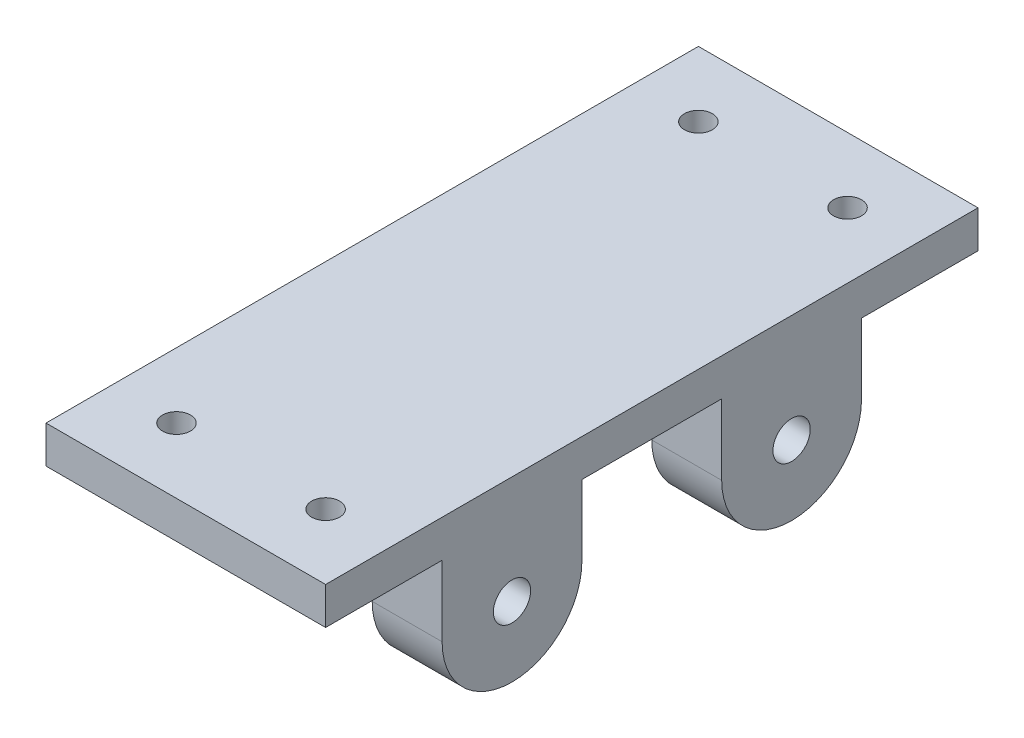
SolidWorks part; units mm, degrees
ref_plane "Front Plane" through (0, 0, 0) normal (0, 0, 1) x (1, 0, 0)
ref_plane "Top Plane" through (0, 0, 0) normal (0, 1, 0) x (1, 0, 0)
ref_plane "Right Plane" through (0, 0, 0) normal (1, 0, 0) x (0, 0, -1)
sketch "Sketch1" plane through (0, 0, 0) normal (0, 1, 0) x (1, 0, 0)
  line L1 (-30, -70) -> (30, -70)
  line L2 (-30, -70) -> (-30, 70)
  line L3 (-30, 70) -> (30, 70)
  line L4 (30, -70) -> (30, 70)
  line L5 (-30, -70) -> (30, 70) construction
  line L6 (-30, 70) -> (30, -70) construction
  point P0 (0, 0)
  dimension "D1" = 140
  dimension "D2" = 60
extrude "Boss-Extrude1" add sketch "Sketch1" along normal blind 8
sketch "Sketch3" plane through (30, 0, 0) normal (1, 0, 0) x (0, 0, -1)
  line L0 (-70, 0) -> (30, 0) construction
  line L1 (-70, 0) -> (70, 0) construction
  line L2 (30, 0) -> (30, -15.1461) construction
  line L3 (15, -15.1461) -> (15, 0)
  line L4 (15, 0) -> (45, 0)
  line L5 (45, 0) -> (45, -15.1461)
  arc A0 (15, -15.1461) -> (45, -15.1461) centre (30, -15.1461) ccw
  dimension "D2" = 15.1461
  dimension "D3" = 15
  dimension "D1" = 30
extrude "Boss-Extrude2" add sketch "Sketch3" against normal up to surface (60 mm away) up to face at (-30, 4, 0)
mirror "Mirror1" about plane through (0, 0, 0) normal (0, 0, 1) of "Boss-Extrude2"
sketch "Sketch5" plane through (30, 0, 0) normal (1, 0, 0) x (0, 0, -1)
  circle A0 centre (30, -15.1461) radius 4
  circle A1 centre (-30, -15.1461) radius 4
  dimension "D1" = 8
extrude "Cut-Extrude1" cut sketch "Sketch5" against normal up to next
sketch "Sketch6" plane through (0, 0, 70) normal (0, 0, 1) x (1, 0, 0)
  line L0 (-30, 0) -> (30, 0) construction
  line L1 (-15, 0) -> (15, 0)
  line L2 (-15, 0) -> (-15, -30.1461)
  line L3 (-15, -30.1461) -> (15, -30.1461)
  line L4 (15, 0) -> (15, -30.1461)
  line L5 (-30, -30.1461) -> (30, -30.1461) construction
  point P8 (0, 0)
  dimension "D1" = 30
extrude "Cut-Extrude2" cut sketch "Sketch6" against normal through all
sketch "Sketch7" plane through (0, 0, 0) normal (0, -1, 0) x (1, 0, 0)
  line L0 (-30, -70) -> (-30, -45) construction
  line L1 (30, -70) -> (-30, -70) construction
  line L2 (20.9804, 0) -> (-20.9804, 0) construction
  line L3 (0, -20.9804) -> (0, 20.9804) construction
  circle A0 centre (-16, -56) radius 3
  circle A1 centre (-16, 56) radius 3
  circle A2 centre (16, 56) radius 3
  circle A3 centre (16, -56) radius 3
  point P2 (0, 0)
  point P5 (0, 0)
  point P7 (-17.946, -68.901)
  dimension "D1" = 6
  dimension "D2" = 14
  dimension "D3" = 14
extrude "Cut-Extrude3" cut sketch "Sketch7" against normal blind 10
